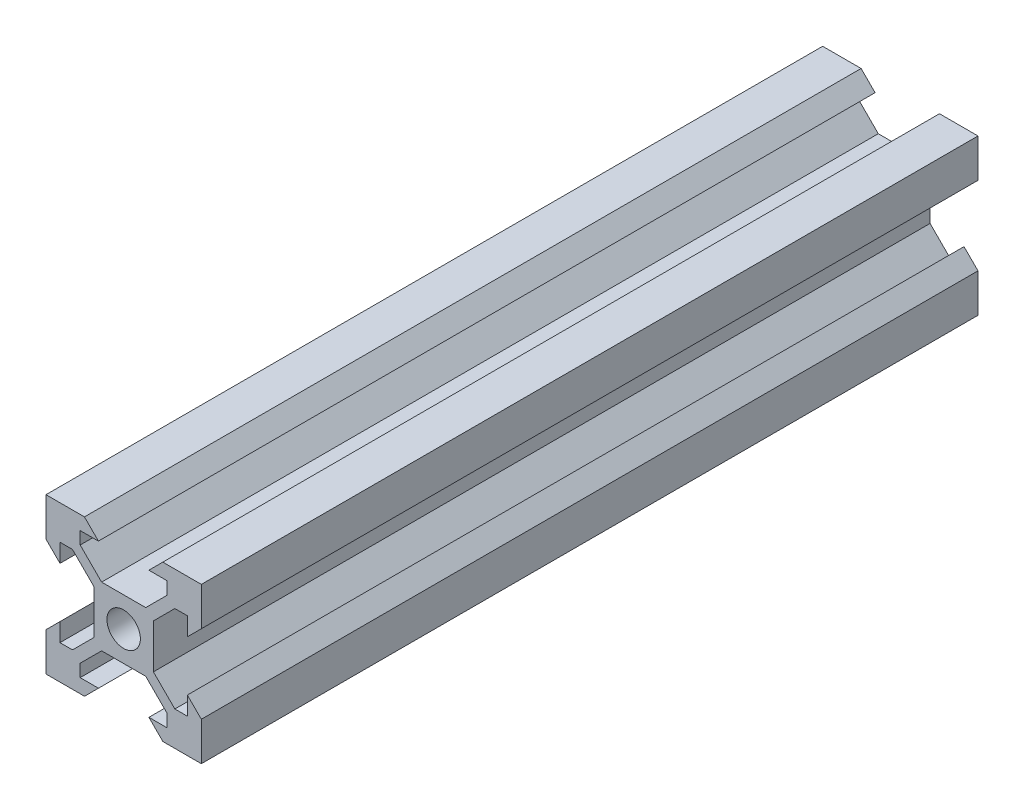
SolidWorks part; units mm, degrees
ref_plane "Alzado" through (0, 0, 0) normal (0, 0, 1) x (1, 0, 0)
ref_plane "Planta" through (0, 0, 0) normal (0, 1, 0) x (1, 0, 0)
ref_plane "Vista lateral" through (0, 0, 0) normal (1, 0, 0) x (0, 0, -1)
sketch "Croquis1" plane through (0, 0, 0) normal (0, 0, 1) x (1, 0, 0)
  line L58 (-1.915, -1.915) -> (-2.8, -2.8) construction
  line L66 (0, 0) -> (-1.915, 0)
  line L72 (0, 0) -> (0, -1.915)
  line L73 (-2.52, -5) -> (-5, -5)
  line L74 (-5, -2.525) -> (-5, -5)
  line L79 (-1.42, -1.915) -> (-2.8, -3.295)
  line L80 (-5, -5) -> (-2.8, -5)
  line L81 (-5, -5) -> (-5, -2.8)
  line L82 (-4.1, -2.8) -> (-3.295, -2.8)
  line L83 (-2.8, -4.1) -> (-2.8, -3.295)
  line L84 (0, 0) -> (-1.915, 0)
  line L85 (0, 0) -> (0, -1.915)
  line L86 (0, -1.915) -> (-1.42, -1.915)
  line L87 (-1.915, 0) -> (-1.915, -1.42)
  line L88 (-1.915, -1.42) -> (-3.295, -2.8)
  line L90 (-1.6675, -2.1625) -> (-2.5525, -3.0475) construction
  line L91 (-2.1625, -1.6675) -> (-3.0475, -2.5525) construction
  line L92 (-5, -2.8) -> (-5, -2.525)
  line L93 (-5, -2.525) -> (-4.1, -1.625)
  line L94 (-4.1, -1.625) -> (-4.1, -2.8)
  line L95 (-2.8, -5) -> (-2.52, -5)
  line L96 (-2.52, -5) -> (-1.62, -4.1)
  line L97 (-1.62, -4.1) -> (-2.8, -4.1)
  line L98 (0, 0) -> (0, 1.915)
  line L99 (0, 0) -> (-1.915, 0)
  line L100 (-5, 2.52) -> (-5, 5)
  line L101 (-2.525, 5) -> (-5, 5)
  line L102 (-1.915, 1.42) -> (-3.295, 2.8)
  line L103 (-5, 5) -> (-5, 2.8)
  line L104 (-5, 5) -> (-2.8, 5)
  line L105 (-2.8, 4.1) -> (-2.8, 3.295)
  line L106 (-4.1, 2.8) -> (-3.295, 2.8)
  line L107 (0, 0) -> (0, 1.915)
  line L108 (0, 0) -> (-1.915, 0)
  line L109 (-1.915, 0) -> (-1.915, 1.42)
  line L110 (0, 1.915) -> (-1.42, 1.915)
  line L111 (-1.42, 1.915) -> (-2.8, 3.295)
  line L112 (-2.8, 5) -> (-2.525, 5)
  line L113 (-2.525, 5) -> (-1.625, 4.1)
  line L114 (-1.625, 4.1) -> (-2.8, 4.1)
  line L115 (-5, 2.8) -> (-5, 2.52)
  line L116 (-5, 2.52) -> (-4.1, 1.62)
  line L117 (-4.1, 1.62) -> (-4.1, 2.8)
  line L118 (-1.915, 1.915) -> (-2.8, 2.8) construction
  line L119 (0, 0) -> (1.915, 0)
  line L120 (0, 0) -> (0, 1.915)
  line L121 (2.52, 5) -> (5, 5)
  line L122 (5, 2.525) -> (5, 5)
  line L123 (1.42, 1.915) -> (2.8, 3.295)
  line L124 (5, 5) -> (2.8, 5)
  line L125 (5, 5) -> (5, 2.8)
  line L126 (4.1, 2.8) -> (3.295, 2.8)
  line L127 (2.8, 4.1) -> (2.8, 3.295)
  line L128 (0, 0) -> (1.915, 0)
  line L129 (0, 0) -> (0, 1.915)
  line L130 (0, 1.915) -> (1.42, 1.915)
  line L131 (1.915, 0) -> (1.915, 1.42)
  line L132 (1.915, 1.42) -> (3.295, 2.8)
  line L133 (5, 2.8) -> (5, 2.525)
  line L134 (5, 2.525) -> (4.1, 1.625)
  line L135 (4.1, 1.625) -> (4.1, 2.8)
  line L136 (2.8, 5) -> (2.52, 5)
  line L137 (2.52, 5) -> (1.62, 4.1)
  line L138 (1.62, 4.1) -> (2.8, 4.1)
  line L139 (1.915, 1.915) -> (2.8, 2.8) construction
  line L140 (0, 0) -> (0, -1.915)
  line L141 (0, 0) -> (1.915, 0)
  line L142 (5, -2.52) -> (5, -5)
  line L143 (2.525, -5) -> (5, -5)
  line L144 (1.915, -1.42) -> (3.295, -2.8)
  line L145 (5, -5) -> (5, -2.8)
  line L146 (5, -5) -> (2.8, -5)
  line L147 (2.8, -4.1) -> (2.8, -3.295)
  line L148 (4.1, -2.8) -> (3.295, -2.8)
  line L149 (0, 0) -> (0, -1.915)
  line L150 (0, 0) -> (1.915, 0)
  line L151 (1.915, 0) -> (1.915, -1.42)
  line L152 (0, -1.915) -> (1.42, -1.915)
  line L153 (1.42, -1.915) -> (2.8, -3.295)
  line L154 (2.8, -5) -> (2.525, -5)
  line L155 (2.525, -5) -> (1.625, -4.1)
  line L156 (1.625, -4.1) -> (2.8, -4.1)
  line L157 (5, -2.8) -> (5, -2.52)
  line L158 (5, -2.52) -> (4.1, -1.62)
  line L159 (4.1, -1.62) -> (4.1, -2.8)
  line L160 (1.915, -1.915) -> (2.8, -2.8) construction
  circle A3 centre (0, 0) radius 1.075
  circle A4 centre (0, 0) radius 1.075
  circle A5 centre (0, 0) radius 1.075
  circle A6 centre (0, 0) radius 1.075
  point P83 (0, 0)
  dimension "D3" = 2.15
  dimension "D20" = 0.9
  dimension "D5" = 10
  dimension "D4" = 4
  dimension "D10" = 2.2
  dimension "D6" = 10
  dimension "D14" = 1.915
  dimension "D15" = 0.35
  dimension "D17" = 0.35
  dimension "D18" = 1.175
  dimension "D21" = 0.275
  dimension "D22" = 0.9
  dimension "D23" = 0.28
  dimension "D24" = 1.18
extrude "Saliente-Extruir1" add sketch "Croquis1" along normal blind 50 contours A3 L129 L110 L111 L105 L114 L113 L101 L100 L116 L117 L106 L102 L109 L108 | A3 L150 L131 L132 L126 L135 L134 L122 L121 L137 L138 L127 L123 L130 L129 | A3 L149 L152 L153 L147 L156 L155 L143 L142 L158 L159 L148 L144 L151 L150 | A3 L108 L87 L88 L82 L94 L93 L74 L73 L96 L97 L83 L79 L86 L149
